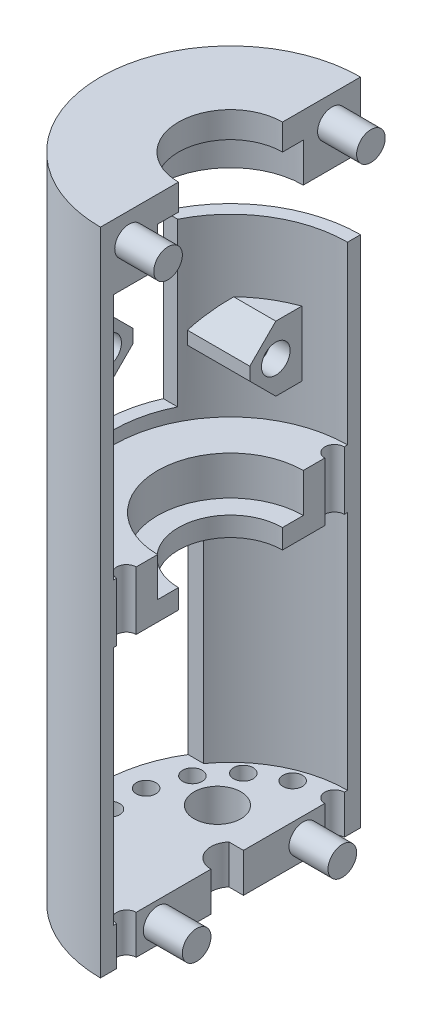
SolidWorks part; units mm, degrees
ref_plane "前视基准面" through (0, 0, 0) normal (0, 0, 1) x (1, 0, 0)
ref_plane "上视基准面" through (0, 0, 0) normal (0, 1, 0) x (1, 0, 0)
ref_plane "右视基准面" through (0, 0, 0) normal (1, 0, 0) x (0, 0, -1)
sketch "草图1" plane through (0, 0, 0) normal (0, 1, 0) x (1, 0, 0)
  line L1 (1.118, 1) -> (-1.118, 1)
  circle A0 centre (0, 0) radius 10
  arc A2 (1.118, 1) -> (-1.118, 1) centre (0, 0) cw
extrude "凸台-拉伸1" add sketch "草图1" along normal blind 3
sketch "草图2" plane through (0, 3, 0) normal (0, 1, 0) x (1, 0, 0)
  line L1 (0, 0) -> (0, 8) construction
  circle A18 centre (0, 8) radius 0.75
  circle A19 centre (2.7362, 7.5175) radius 0.75
  circle A20 centre (5.1423, 6.1284) radius 0.75
  circle A21 centre (6.9282, 4) radius 0.75
  circle A22 centre (7.8785, 1.3892) radius 0.75
  circle A23 centre (7.8785, -1.3892) radius 0.75
  circle A24 centre (6.9282, -4) radius 0.75
  circle A25 centre (5.1423, -6.1284) radius 0.75
  circle A26 centre (2.7362, -7.5175) radius 0.75
  circle A27 centre (0, -8) radius 0.75
  circle A28 centre (-2.7362, -7.5175) radius 0.75
  circle A29 centre (-5.1423, -6.1284) radius 0.75
  circle A30 centre (-6.9282, -4) radius 0.75
  circle A31 centre (-7.8785, -1.3892) radius 0.75
  circle A32 centre (-7.8785, 1.3892) radius 0.75
  circle A33 centre (-6.9282, 4) radius 0.75
  circle A34 centre (-5.1423, 6.1284) radius 0.75
  circle A35 centre (-2.7362, 7.5175) radius 0.75
  point P41 (0, 0)
  point P42 (0, 0)
extrude "切除-拉伸1" cut sketch "草图2" against normal up to next
sketch "草图3" plane through (0, 3, 0) normal (0, 1, 0) x (1, 0, 0)
  circle A0 centre (0, 0) radius 10
  circle A1 centre (0, 0) radius 9
extrude "凸台-拉伸2" add sketch "草图3" along normal blind 47
sketch "草图4" plane through (0, 50, 0) normal (0, 1, 0) x (1, 0, 0)
  line L0 (0, -10) -> (0, 10)
  circle A0 centre (0, 0) radius 10 construction
  arc A1 (0, -10) -> (0, 10) centre (0, 0) ccw
extrude "切除-拉伸2" cut sketch "草图4" against normal blind 50
ref_plane "基准面4" through (0, 29, 0) normal (0, 1, 0) x (1, 0, 0)
ref_plane "基准面5" through (0, 41, 0) normal (0, 1, 0) x (1, 0, 0)
sketch "草图9" plane through (0, 0, 0) normal (0, -1, 0) x (1, 0, 0)
  line L1 (0, 9) -> (0, 5.6)
  line L2 (0, -5.6) -> (0, -9)
  arc A3 (0, 9) -> (0, -9) centre (0, 0) ccw
  arc A4 (0, 5.6) -> (0, -5.6) centre (0, 0) ccw
extrude "凸台-拉伸5" add sketch "草图9" against normal blind 3 from offset 23 offset against normal yes
sketch "草图10" plane through (0, 23, 0) normal (0, -1, 0) x (1, 0, 0)
  line L1 (0, 9) -> (0, 4)
  line L2 (0, -4) -> (0, -9)
  arc A2 (0, 9) -> (0, -9) centre (0, 0) ccw
  arc A3 (0, 4) -> (0, -4) centre (0, 0) ccw
extrude "凸台-拉伸6" add sketch "草图10" along normal blind 1.5
sketch "草图11" plane through (0, 50, 0) normal (0, 1, 0) x (1, 0, 0)
  line L2 (0, -9) -> (0, -4)
  line L3 (0, 4) -> (0, 9)
  arc A2 (0, -9) -> (0, 9) centre (0, 0) cw
  arc A3 (0, -4) -> (0, 4) centre (0, 0) cw
extrude "凸台-拉伸7" add sketch "草图11" against normal blind 2
sketch "草图12" plane through (0, 48, 0) normal (0, -1, 0) x (1, 0, 0)
  line L1 (0, 9) -> (0, 5.6)
  line L2 (0, -5.6) -> (0, -9)
  arc A2 (0, 9) -> (0, -9) centre (0, 0) ccw
  arc A3 (0, 5.6) -> (0, -5.6) centre (0, 0) ccw
extrude "凸台-拉伸8" add sketch "草图12" along normal blind 3
sketch "草图13" plane through (0, 26, 0) normal (0, 1, 0) x (1, 0, 0)
  circle A0 centre (0, 0) radius 8 construction
  circle A1 centre (0, 8) radius 0.75
  circle A2 centre (0, -8) radius 0.75
extrude "切除-拉伸5" cut sketch "草图13" against normal through all
sketch "草图14" plane through (0, 0, 0) normal (1, 0, 0) x (0, 0, -1)
  line L0 (-1.5, 3) -> (-7.25, 3) construction
  line L1 (5.25, 21.5) -> (-4.375, 21.5)
  line L2 (5.25, 21.5) -> (5.25, 3)
  line L3 (5.25, 3) -> (-4.375, 3)
  line L4 (-4.375, 21.5) -> (-4.375, 3)
  line L5 (5.25, 21.5) -> (-4.375, 3) construction
  line L6 (5.25, 3) -> (-4.375, 21.5) construction
  line L7 (-4, 21.5) -> (-7.25, 21.5) construction
  point P0 (0.4375, 12.25)
extrude "切除-拉伸6" cut sketch "草图14" against normal up to next
sketch "草图15" plane through (0, 0, 0) normal (1, 0, 0) x (0, 0, -1)
  line L1 (3.6373, 45) -> (-4, 45)
  line L3 (4, 27) -> (-4, 27)
  line L4 (-4, 45) -> (-4, 27)
  line L5 (3.6373, 45) -> (-4, 27) construction
  line L6 (4, 27) -> (-4, 45) construction
  line L12 (10, 0) -> (10, 50) construction
  line L14 (10, 45) -> (3.6373, 45)
  line L15 (10, 45) -> (10, 39.5)
  line L16 (10, 39.5) -> (4, 39.5)
  line L17 (4, 39.5) -> (4, 27)
  point P0 (-0.0928, 36.2088)
extrude "切除-拉伸7" cut sketch "草图15" against normal up to next
sketch "草图16" plane through (0, 0, 0) normal (1, 0, 0) x (0, 0, -1)
  circle A0 centre (-7.8, 48) radius 1.1
  circle A1 centre (7.8, 48) radius 1.1
  circle A2 centre (-5.6, 1.5) radius 1.1
  circle A3 centre (5.6, 1.5) radius 1.1
extrude "凸台-拉伸9" add sketch "草图16" along normal blind 3
sketch "Sketch1" plane through (0, 29, 0) normal (0, 1, 0) x (1, 0, 0)
  line L0 (-3, 4.4853) -> (-7.8027, 4.4853)
  line L1 (-3, 8.4853) -> (-3, 4.4853)
  arc A1 (-3, 8.4853) -> (-7.8027, 4.4853) centre (0, 0) ccw
extrude "Boss-Extrude1" add sketch "Sketch1" along normal blind 5
sketch "Sketch2" plane through (0, 41, 0) normal (0, 1, 0) x (1, 0, 0)
  line L0 (-3, -4.4853) -> (-7.8027, -4.4853)
  line L1 (-3, -8.4853) -> (-3, -4.4853)
  arc A1 (-7.8027, -4.4853) -> (-3, -8.4853) centre (0, 0) ccw
extrude "Boss-Extrude2" add sketch "Sketch2" against normal blind 5
sketch "Sketch3" plane through (-3, 0, 0) normal (1, 0, 0) x (0, 0, -1)
  circle A0 centre (-6.4853, 38.5) radius 1.1
  circle A1 centre (6.4853, 31.5) radius 1.1
extrude "Cut-Extrude1" cut sketch "Sketch3" against normal blind 1.5
chamfer "Chamfer1" distance 2 angle 45 4 edges at (-5.4014, 29, -4.4853) (-5.4014, 34, -4.4853) (-5.4014, 36, 4.4853) (-5.4014, 41, 4.4853)
sketch "Sketch4" plane through (0, 0, 0) normal (0, -1, 0) x (1, 0, 0)
  circle A0 centre (-4, -3) radius 1.8
extrude "Cut-Extrude2" cut sketch "Sketch4" against normal up to next
